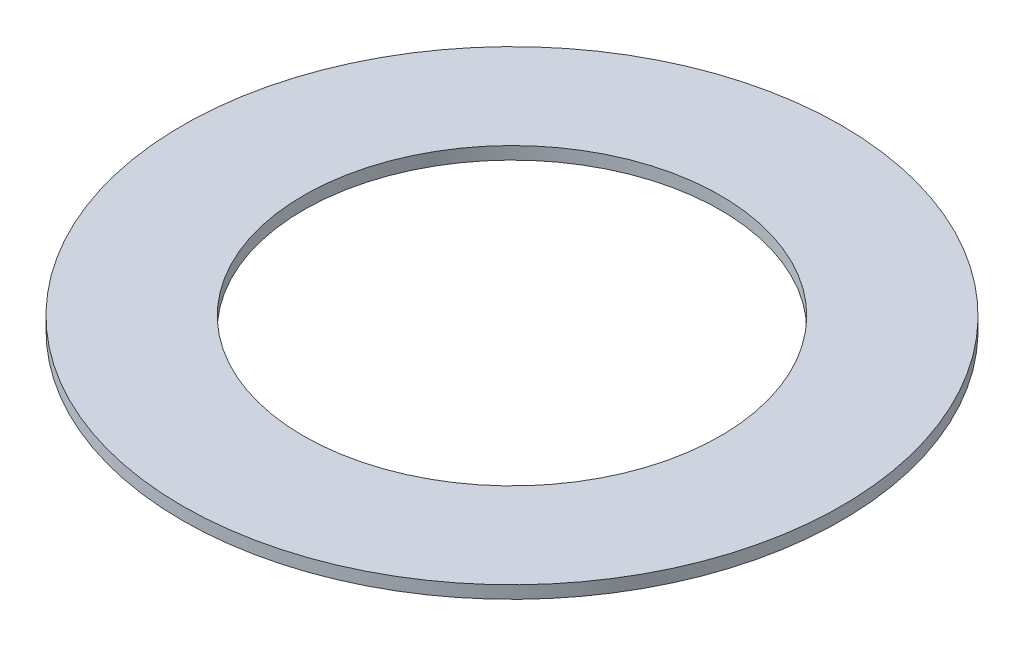
SolidWorks part; units mm, degrees
ref_plane "Front Plane" through (0, 0, 0) normal (0, 0, 1) x (1, 0, 0)
ref_plane "Top Plane" through (0, 0, 0) normal (0, 1, 0) x (1, 0, 0)
ref_plane "Right Plane" through (0, 0, 0) normal (1, 0, 0) x (0, 0, -1)
sketch "Sketch1" plane through (0, 0, 0) normal (0, 1, 0) x (1, 0, 0)
  circle A0 centre (0, 0) radius 78.35
  circle A1 centre (0, 0) radius 49.55
  dimension "D1" = 156.7
  dimension "D2" = 99.1
extrude "Boss-Extrude1" add sketch "Sketch1" along normal blind 3
